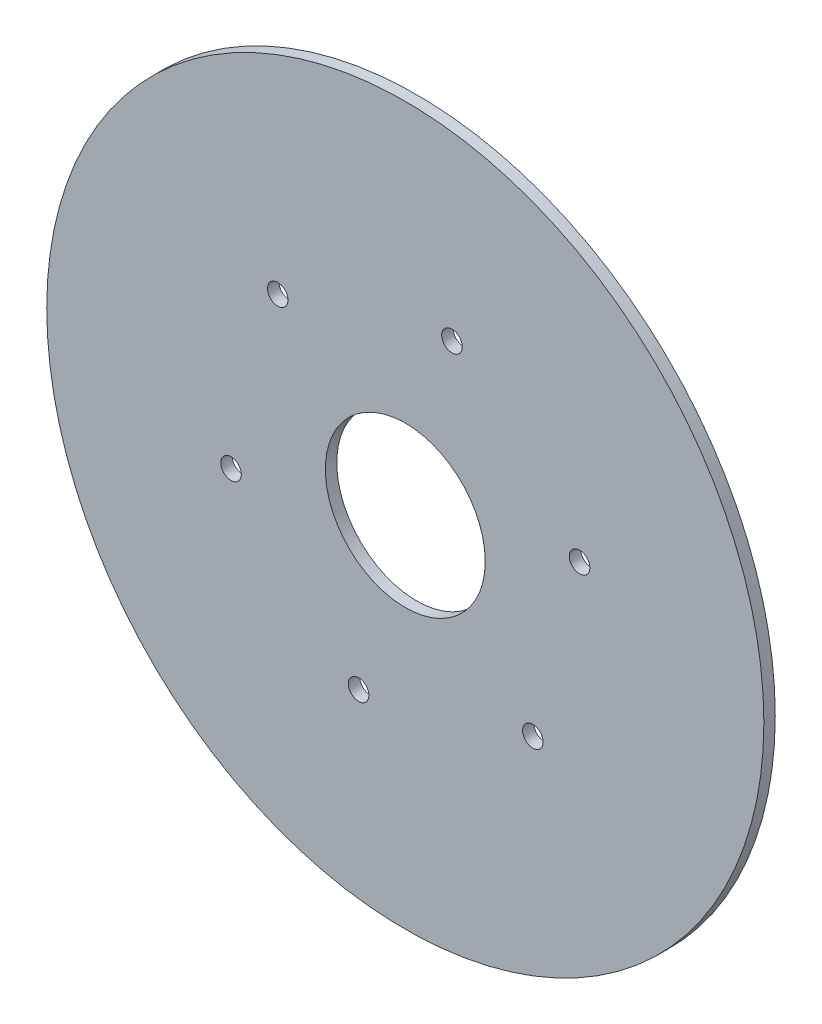
SolidWorks part; units mm, degrees
ref_plane "Спереди" through (0, 0, 0) normal (0, 0, 1) x (1, 0, 0)
ref_plane "Сверху" through (0, 0, 0) normal (0, 1, 0) x (1, 0, 0)
ref_plane "Справа" through (0, 0, 0) normal (1, 0, 0) x (0, 0, -1)
sketch "Эскиз1" plane through (0, 0, 0) normal (0, 0, 1) x (1, 0, 0)
  circle A0 centre (0, 0) radius 78.5
  circle A1 centre (0, 0) radius 17.5
extrude "Front_cover_reference" add sketch "Эскиз1" along normal blind 2.5 from offset 58.5
sketch "Эскиз2" plane through (0, 0, 0) normal (0, 0, 1) x (1, 0, 0)
  circle A0 centre (38.1541, 10.2234) radius 2.25
  circle A1 centre (10.2234, 38.1541) radius 2.25
  circle A2 centre (-27.9307, 27.9307) radius 2.25
  circle A3 centre (-38.1541, -10.2234) radius 2.25
  circle A4 centre (-10.2234, -38.1541) radius 2.25
  circle A5 centre (27.9307, -27.9307) radius 2.25
extrude "Through_holes" cut sketch "Эскиз2" against normal mid plane 200
